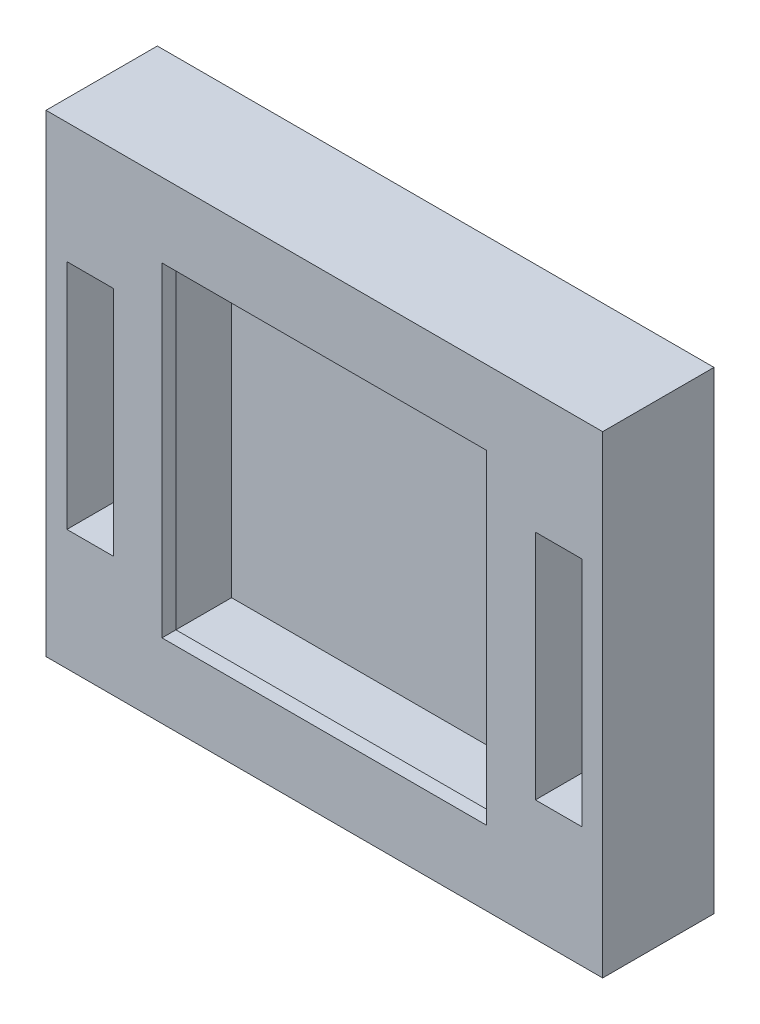
SolidWorks part; units mm, degrees
ref_plane "Front Plane" through (0, 0, 0) normal (0, 0, 1) x (1, 0, 0)
ref_plane "Top Plane" through (0, 0, 0) normal (0, 1, 0) x (1, 0, 0)
ref_plane "Right Plane" through (0, 0, 0) normal (1, 0, 0) x (0, 0, -1)
sketch "Sketch1" plane through (0, 0, 0) normal (0, 0, 1) x (1, 0, 0)
  line L1 (-15.24, -12.954) -> (15.24, -12.954)
  line L2 (-15.24, -12.954) -> (-15.24, 12.954)
  line L3 (-15.24, 12.954) -> (15.24, 12.954)
  line L4 (15.24, -12.954) -> (15.24, 12.954)
  line L5 (-15.24, -12.954) -> (15.24, 12.954) construction
  line L6 (-15.24, 12.954) -> (15.24, -12.954) construction
  point P0 (0, 0)
  dimension "D1" = 30.48
  dimension "D2" = 25.908
extrude "Boss-Extrude1" add sketch "Sketch1" along normal blind 5.334
sketch "Sketch2" plane through (0, 0, 5.334) normal (0, 0, 1) x (1, 0, 0)
  line L0 (-10.414, 0) -> (-15.24, 0) construction
  line L1 (-10.414, -10.414) -> (10.414, -10.414)
  line L2 (-10.414, -10.414) -> (-10.414, 10.414)
  line L3 (-10.414, 10.414) -> (10.414, 10.414)
  line L4 (10.414, -10.414) -> (10.414, 10.414)
  line L5 (-10.414, -10.414) -> (10.414, 10.414) construction
  line L6 (-10.414, 10.414) -> (10.414, -10.414) construction
  line L7 (-15.24, 12.954) -> (-15.24, -12.954) construction
  point P0 (0, 0)
extrude "Cut-Extrude1" cut sketch "Sketch2" against normal blind 4.572
sketch "Sketch3" plane through (0, 0, 5.334) normal (0, 0, 1) x (1, 0, 0)
  line L1 (-15.24, 12.954) -> (15.24, 12.954)
  line L2 (-15.24, 12.954) -> (-15.24, -12.954)
  line L3 (-15.24, -12.954) -> (15.24, -12.954)
  line L4 (15.24, 12.954) -> (15.24, -12.954)
  line L5 (8.89, -8.89) -> (-8.89, -8.89)
  line L6 (8.89, -8.89) -> (8.89, 8.89)
  line L7 (8.89, 8.89) -> (-8.89, 8.89)
  line L8 (-8.89, -8.89) -> (-8.89, 8.89)
  line L9 (8.89, -8.89) -> (-8.89, 8.89) construction
  line L10 (8.89, 8.89) -> (-8.89, -8.89) construction
  point P6 (0, 0)
  dimension "D1" = 17.78
  dimension "D2" = 17.78
extrude "Boss-Extrude2" add sketch "Sketch3" along normal blind 0.762
sketch "Sketch4" plane through (0, 0, 6.096) normal (0, 0, 1) x (1, 0, 0)
  line L0 (0, 0) -> (-8.89, 0) construction
  line L2 (-8.89, 8.89) -> (-8.89, -8.89) construction
  line L4 (-10.414, 0) -> (-15.24, 0) construction
  line L6 (0, 0) -> (8.8735, 0) construction
  line L9 (0, -1000) -> (0, 49000) construction
  line L15 (-10.414, 10.414) -> (-10.414, -10.414) construction
  line L24 (-15.24, 12.954) -> (-15.24, -12.954) construction
  line L25 (11.557, 6.35) -> (14.097, -6.35) construction
  line L26 (-11.557, -6.35) -> (-14.097, -6.35)
  line L27 (-11.557, -6.35) -> (-11.557, 6.35)
  line L32 (-11.557, 6.35) -> (-14.097, 6.35)
  line L33 (-14.097, -6.35) -> (-14.097, 6.35)
  line L34 (-11.557, -6.35) -> (-14.097, 6.35) construction
  line L35 (-11.557, 6.35) -> (-14.097, -6.35) construction
  line L36 (11.557, -6.35) -> (14.097, 6.35) construction
  line L37 (10.414, 0) -> (15.24, 0) construction
  line L38 (14.097, -6.35) -> (14.097, 6.35)
  line L39 (11.557, 6.35) -> (14.097, 6.35)
  line L40 (11.557, -6.35) -> (11.557, 6.35)
  line L41 (11.557, -6.35) -> (14.097, -6.35)
  line L42 (10.414, 10.414) -> (-10.414, 10.414) construction
  line L43 (8.89, 8.89) -> (-8.89, 8.89) construction
  line L44 (15.24, 12.954) -> (-15.24, 12.954) construction
  point P13 (-12.827, 0)
  point P26 (12.827, 0)
  dimension "D1" = 2.54
  dimension "D2" = 12.7
extrude "Cut-Extrude5" cut sketch "Sketch4" against normal through all
